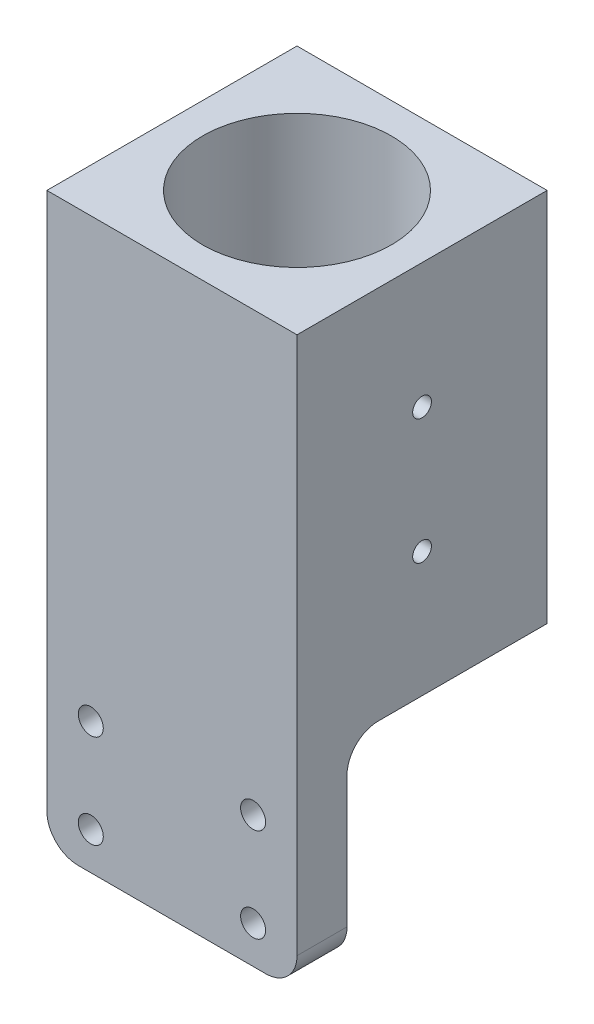
SolidWorks part; units mm, degrees
ref_plane "前基準面" through (0, 0, 0) normal (0, 0, 1) x (1, 0, 0)
ref_plane "上基準面" through (0, 0, 0) normal (0, 1, 0) x (1, 0, 0)
ref_plane "右基準面" through (0, 0, 0) normal (1, 0, 0) x (0, 0, -1)
sketch "草圖1" plane through (0, 0, 0) normal (0, 1, 0) x (1, 0, 0)
  line L1 (-20, 20) -> (20, 20)
  line L2 (-20, 20) -> (-20, -20)
  line L3 (-20, -20) -> (20, -20)
  line L4 (20, 20) -> (20, -20)
  line L5 (-20, 20) -> (20, -20) construction
  line L6 (-20, -20) -> (20, 20) construction
  dimension "D2" = 40
extrude "填料-伸長1" add sketch "草圖1" along normal blind 60
sketch "草圖2" plane through (0, 60, 0) normal (0, 1, 0) x (1, 0, 0)
  circle A0 centre (0, 0) radius 15.1
  dimension "D1" = 30.2
extrude "除料-伸長1" cut sketch "草圖2" against normal blind 50
sketch "草圖3" plane through (0, 0, 20) normal (0, 0, 1) x (1, 0, 0)
  line L2 (-12.98, -10.0044) -> (12.98, -10.0044) construction
  line L3 (-20, 0) -> (20, 0)
  line L4 (-20, 0) -> (-20, -31)
  line L5 (-20, -31) -> (20, -31)
  line L6 (20, 0) -> (20, -31)
  circle A2 centre (-12.98, -10.0044) radius 2
  circle A3 centre (12.98, -10.0044) radius 2
  circle A4 centre (-12.98, -25.0044) radius 2
  circle A5 centre (12.98, -25.0044) radius 2
  point P5 (0, 0)
  point P12 (0, -10.0044)
  dimension "D1" = 40
  dimension "D3" = 4
  dimension "D2" = 31
  dimension "D4" = 10.0044
  dimension "D5" = 25.96
  dimension "D6" = 15
extrude "填料-伸長2" add sketch "草圖3" against normal blind 8
sketch "草圖4" plane through (20, 0, 0) normal (1, 0, 0) x (0, 0, -1)
  circle A0 centre (0, 20) radius 1.5
  dimension "D1" = 3
  dimension "D2" = 20
extrude "除料-伸長2" cut sketch "草圖4" against normal through all
pattern_linear "直線複製排列1" count 2 spacing 20 along (0, 1, 0) of "除料-伸長2"
fillet "圓角1" radius 5 3 edges at (0, 0, 12) (-20, -31, 16) (20, -31, 16)
